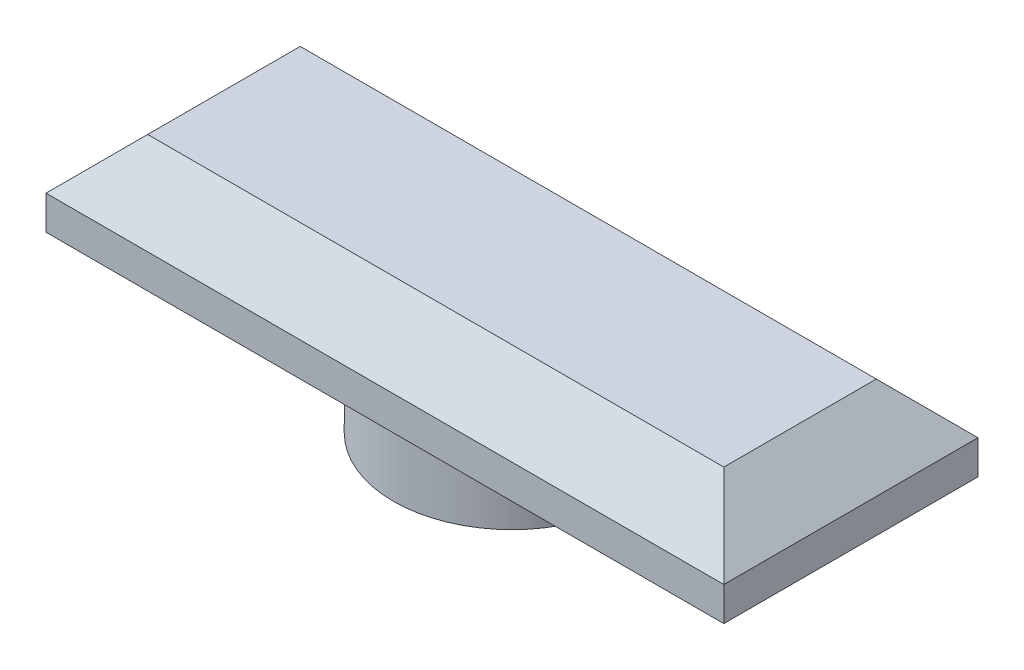
SolidWorks part; units mm, degrees
ref_plane "Front Plane" through (0, 0, 0) normal (0, 0, 1) x (1, 0, 0)
ref_plane "Top Plane" through (0, 0, 0) normal (0, 1, 0) x (1, 0, 0)
ref_plane "Right Plane" through (0, 0, 0) normal (1, 0, 0) x (0, 0, -1)
sketch "Sketch2" plane through (0, 4, 0) normal (0, 1, 0) x (1, 0, 0)
  line L1 (-20, 7.5) -> (20, 7.5)
  line L2 (-20, 7.5) -> (-20, -7.5)
  line L3 (-20, -7.5) -> (20, -7.5)
  line L4 (20, 7.5) -> (20, -7.5)
  line L5 (-20, 7.5) -> (20, -7.5) construction
  line L6 (-20, -7.5) -> (20, 7.5) construction
  point P0 (0, 0)
extrude "Boss-Extrude2" add sketch "Sketch2" along normal blind 5
chamfer "Chamfer1" distance 3 angle 45 4 edges at (20, 9, 0) (0, 9, -7.5) (-20, 9, 0) (0, 9, 7.5)
sketch "Sketch5" plane through (0, 4, 0) normal (0, -1, 0) x (-1, 0, 0)
  circle A0 centre (0, 0) radius 6
  circle A1 centre (0, 0) radius 7
extrude "Boss-Extrude4" add sketch "Sketch5" along normal blind 4
